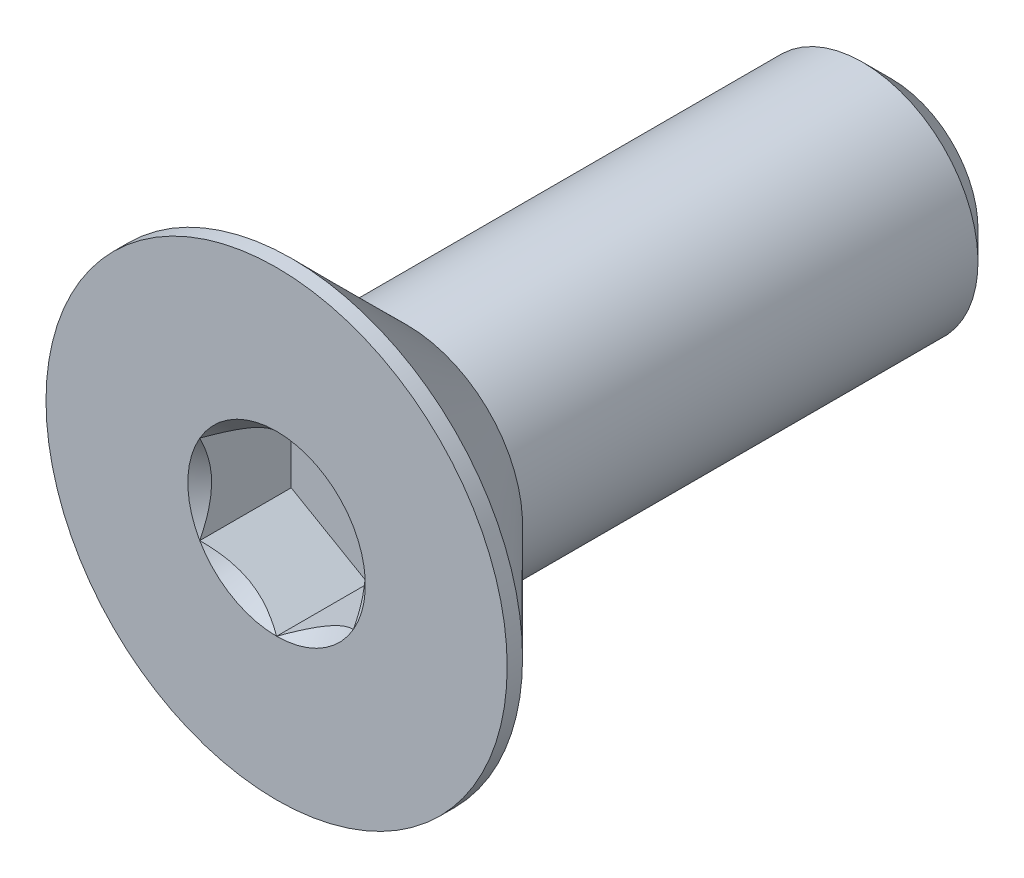
SolidWorks part; units mm, degrees
ref_plane "Front" through (0, 0, 0) normal (0, 0, 1) x (1, 0, 0)
ref_plane "Top" through (0, 0, 0) normal (0, 1, 0) x (1, 0, 0)
ref_plane "Right" through (0, 0, 0) normal (1, 0, 0) x (0, 0, -1)
sketch "Sketch1" plane through (0, 0, 0) normal (1, 0, 0) x (0, 0, -1)
  line L0 (0, 3) -> (0.2, 3) construction
  line L1 (0.2, 3) -> (1.7, 1.5) construction
  line L2 (0, 1.5) -> (8, 1.5)
  line L3 (8, 1.5) -> (8, 0)
  line L4 (8, 0) -> (0, 0)
  line L5 (0, 0) -> (0, 3) construction
  line L6 (0, 3) -> (0, -3) construction
  line L7 (8, 1.5) -> (8, -1.5) construction
  line L8 (0, -3) -> (0.2, -3) construction
  line L9 (0.2, -3) -> (1.7, -1.5) construction
  line L11 (0, 1.5) -> (0, 0)
  line L12 (1.7, 1.5) -> (1.7, 0) construction
revolve "Revolve1" add sketch "Sketch1" angle 360 mid plane about L4
sketch "Sketch3" plane through (0, 0, -8) normal (0, 0, -1) x (-1, 0, 0)
  circle A0 centre (0, 0) radius 1.5
curve "Helix/Spiral1" pitch 0.5 height 8 turns 16
sketch "Sketch2" plane through (0, 0, 0) normal (1, 0, 0) x (0, 0, -1)
  line L0 (8, 1.5) -> (8.4375, 1.5)
  line L1 (8.4375, 1.5) -> (8.25, 1.1752)
  line L2 (8.25, 1.1752) -> (8.1875, 1.1752)
  line L3 (8.1875, 1.1752) -> (8, 1.5)
  line L4 (8.0938, 1.3376) -> (8.3438, 1.3376) construction
  dimension "D1" = 60
  dimension "D2" = 0.0625
  dimension "D3" = 0.25
chamfer "Chamfer1" distance 0.375 angle 45 1 edges at (0, 1.5, -8)
sketch "Sketch7" plane through (0, 0, 0) normal (1, 0, 0) x (0, 0, -1)
  line L0 (0, 3) -> (0.2, 3) construction
  line L1 (0.2, 3) -> (1.7, 1.5) construction
  line L2 (0, 3) -> (0.2, 3)
  line L3 (0.2, 3) -> (1.7, 1.5)
  line L4 (1.7, 1.5) -> (1.7, 0) construction
  line L5 (1.7, 1.5) -> (1.7, 0)
  line L7 (0, 0) -> (0, 3) construction
  line L8 (0, 0) -> (0, 3)
  line L9 (0, 0) -> (1.7, 0)
  line L10 (3.3, 0) -> (-3.3, 0) construction
revolve "Revolve2" add sketch "Sketch7" angle 360 mid plane about L9
ref_plane "Plane1" through (0, 0, -1.7) normal (0, 0, 1) x (1, 0, 0)
sketch "Sketch8" plane through (0, 0, -1.7) normal (0, 0, 1) x (1, 0, 0)
  circle A0 centre (0, 0) radius 1.5
extrude "Boss-Extrude1" add sketch "Sketch8" against normal through all draft 45
sketch "Sketch5" plane through (0, 0, 0) normal (0, 0, 1) x (1, 0, 0)
  line L1 (1, -0.5774) -> (1, 0.5774)
  line L2 (1, 0.5774) -> (0, 1.1547)
  line L3 (0, 1.1547) -> (-1, 0.5774)
  line L4 (-1, 0.5774) -> (-1, -0.5774)
  line L5 (-1, -0.5774) -> (0, -1.1547)
  line L6 (0, -1.1547) -> (1, -0.5774)
  circle A0 centre (0, 0) radius 1 construction
  dimension "Hex" = 2
extrude "Cut-Extrude2" cut sketch "Sketch5" against normal blind 1.19
sketch "Sketch6" plane through (0, 0, 0) normal (0, 0, 1) x (1, 0, 0)
  circle A0 centre (0, 0) radius 1.1547
extrude "Cut-Extrude3" cut sketch "Sketch6" against normal blind 1.19 draft 45
sketch "Sketch9" [suppressed] plane through (0, 0, -1.5) normal (0, 0, 1) x (1, 0, 0)
  circle A1 centre (0, 0) radius 1.25
  circle A2 centre (0, 0) radius 1.25
  point P0 (0, 1.25)
  dimension "D1" = 0
extrude "Boss-Extrude2" [suppressed] add sketch "Sketch9" against normal offset from surface (3.5 mm away) 26
fillet "Fillet1" [suppressed] radius 0.3
sketch "Sketch10" plane through (0, 0, 0) normal (1, 0, 0) x (0, 0, -1)
  line L0 (8, 1.5) -> (8, -1.5) construction
  point P0 (7.25, -1.5)
  dimension "D1" = 0.75
equation "\"D3@Helix/Spiral1\" = \"Lg@Sketch1\""
equation "\"D2@Sketch2\" = \"D4@Helix/Spiral1\" * .125"
equation "\"D3@Sketch2\" = \"D4@Helix/Spiral1\" * .5"
equation "\"D1@Chamfer1\" = \"D4@Helix/Spiral1\" * .75"
equation "\"D1@Cut-Extrude2\" = \"Head Ht@Sketch1\" * .7"
equation "\"D1@Sketch10\" = \"D4@Helix/Spiral1\" * 1.5"
equation "\"D1@Cut-Extrude3\" = \"D1@Cut-Extrude2\""
equation "\"D1@Fillet1\" = \"Dia@Sketch1\" * .1"
